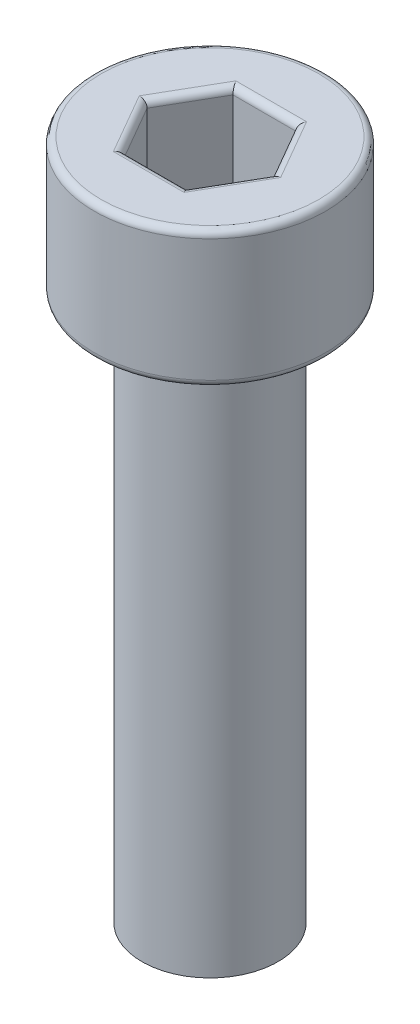
SolidWorks part; units mm, degrees
ref_plane "Front Plane" through (0, 0, 0) normal (0, 0, 1) x (1, 0, 0)
ref_plane "Top Plane" through (0, 0, 0) normal (0, 1, 0) x (1, 0, 0)
ref_plane "Right Plane" through (0, 0, 0) normal (1, 0, 0) x (0, 0, -1)
sketch "Sketch1" plane through (0, 0, 0) normal (0, 0, 1) x (1, 0, 0)
  line L0 (0, 21.3223) -> (0, -43.638) construction
sketch "Sketch2" plane through (0, 0, 0) normal (0, 0, 1) x (1, 0, 0)
  line L0 (0, 5) -> (4.25, 5)
  line L1 (0, 200021.3223) -> (0, -200043.638) construction
  line L2 (4.25, 5) -> (4.25, 0)
  line L3 (4.25, 0) -> (2.5, 0)
  line L4 (2.5, 0) -> (2.5, -20)
  line L5 (2.5, -20) -> (0, -20)
  line L6 (0, -20) -> (0, 5)
  dimension "D1" = 2.5
  dimension "D2" = 4.25
  dimension "D3" = 5
  dimension "D4" = 20
revolve "Revolve1" add sketch "Sketch2" angle 360 about L0
sketch "Sketch3" plane through (0, 5, 0) normal (0, 1, 0) x (1, 0, 0)
  line L0 (0, 0) -> (2.3094, 0) construction
  line L1 (2.3094, 0) -> (1.1547, 2)
  line L2 (1.1547, 2) -> (-1.1547, 2)
  line L3 (-1.1547, 2) -> (-2.3094, 0)
  line L4 (-2.3094, 0) -> (-1.1547, -2)
  line L5 (-1.1547, -2) -> (1.1547, -2)
  line L6 (1.1547, -2) -> (2.3094, 0)
  circle A0 centre (0, 0) radius 2 construction
  dimension "D1" = 4
extrude "Cut-Extrude1" cut sketch "Sketch3" against normal blind 3.5
fillet "Fillet1" radius 0.25 9 edges at (-2.5, 0, 0) (-4.25, 0, 0) (-4.25, 5, 0) (0, 5, -2) (-1.7321, 5, -1) (-1.7321, 5, 1) (0, 5, 2) (1.7321, 5, 1) (1.7321, 5, -1)
